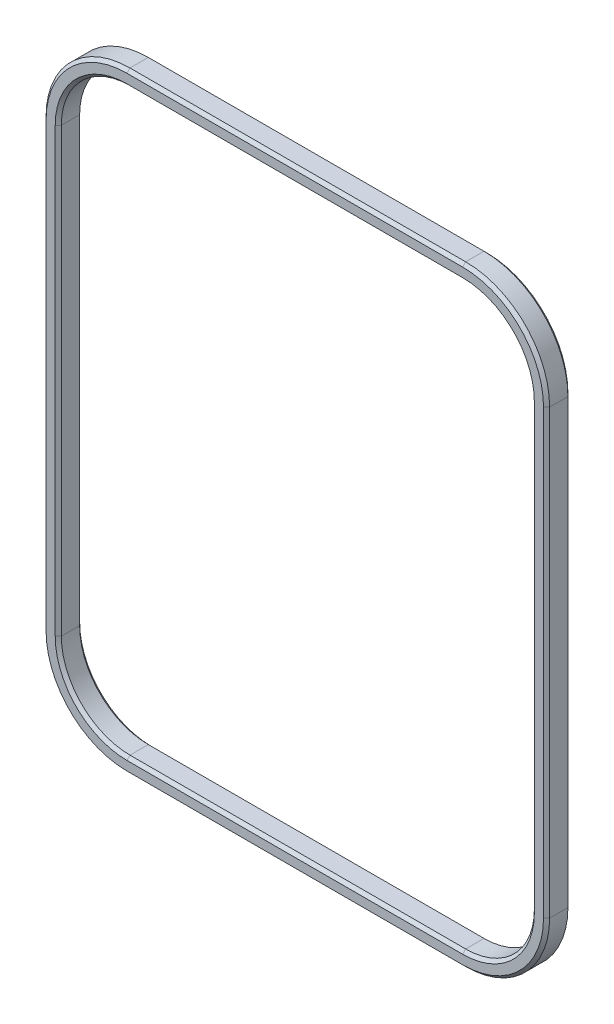
SolidWorks part; units mm, degrees
ref_plane "Ebene vorne" through (0, 0, 0) normal (1, 0, 0) x (0, 1, 0)
ref_plane "Ebene oben" through (0, 0, 0) normal (0, 0, 1) x (0, 1, 0)
ref_plane "Ebene rechts" through (0, 0, 0) normal (0, 1, 0) x (-1, 0, 0)
sketch "Skizze1" plane through (0, 0, 0) normal (0, 0, 1) x (0, 1, 0)
  line L0 (-20, -11) -> (-20, 11)
  line L1 (-14.5, -15.5) -> (14.5, -15.5)
  line L2 (-19, -11) -> (-19, 11)
  line L3 (-14.5, 15.5) -> (14.5, 15.5)
  line L4 (19, -11) -> (19, 11)
  line L5 (-17.682, -14.182) -> (17.682, 14.182) construction
  line L6 (-17.682, 14.182) -> (17.682, -14.182) construction
  line L7 (-14.5, -16.5) -> (14.5, -16.5)
  line L8 (20, -11) -> (20, 11)
  line L9 (-14.5, 16.5) -> (14.5, 16.5)
  arc A0 (-14.5, 15.5) -> (-19, 11) centre (-14.5, 11) ccw
  arc A1 (19, 11) -> (14.5, 15.5) centre (14.5, 11) ccw
  arc A2 (-19, -11) -> (-14.5, -15.5) centre (-14.5, -11) ccw
  arc A3 (14.5, -15.5) -> (19, -11) centre (14.5, -11) ccw
  arc A4 (-14.5, 16.5) -> (-20, 11) centre (-14.5, 11) ccw
  arc A5 (-20, -11) -> (-14.5, -16.5) centre (-14.5, -11) ccw
  arc A6 (14.5, -16.5) -> (20, -11) centre (14.5, -11) ccw
  arc A7 (20, 11) -> (14.5, 16.5) centre (14.5, 11) ccw
  point P0 (0, 0)
  point P2 (0, 0)
  point P7 (-17.682, 14.182)
  point P9 (0, 0)
  point P11 (17.682, 14.182)
  point P13 (0, 0)
  point P23 (-17.682, -14.182)
  point P24 (0, 0)
  point P25 (17.682, -14.182)
  dimension "D3" = 4.5
  dimension "D1" = 38
  dimension "D2" = 31
  dimension "D4" = 1
extrude "Aufsatz-Linear austragen1" add sketch "Skizze1" along normal blind 1.6
chamfer "Fase1" distance 0.2 angle 45 32 edges at (15.5, 0, 0) (14.182, -17.682, 0) (0, -19, 0) (-14.182, -17.682, 0) (-15.5, 0, 0) (-14.182, 17.682, 0) (0, 19, 0) (14.182, 17.682, 0) (0, -20, 0) (14.8891, -18.3891, 0) (16.5, 0, 0) (14.8891, 18.3891, 0) (0, 20, 0) (-14.8891, 18.3891, 0) (-16.5, 0, 0) (-14.8891, -18.3891, 0) (-14.182, 17.682, 1.6) (-15.5, 0, 1.6) (-14.182, -17.682, 1.6) (0, -19, 1.6) (14.182, -17.682, 1.6) (15.5, 0, 1.6) (14.182, 17.682, 1.6) (0, 19, 1.6) (-16.5, 0, 1.6) (-14.8891, 18.3891, 1.6) (0, 20, 1.6) (14.8891, 18.3891, 1.6) (16.5, 0, 1.6) (14.8891, -18.3891, 1.6) (0, -20, 1.6) (-14.8891, -18.3891, 1.6)
